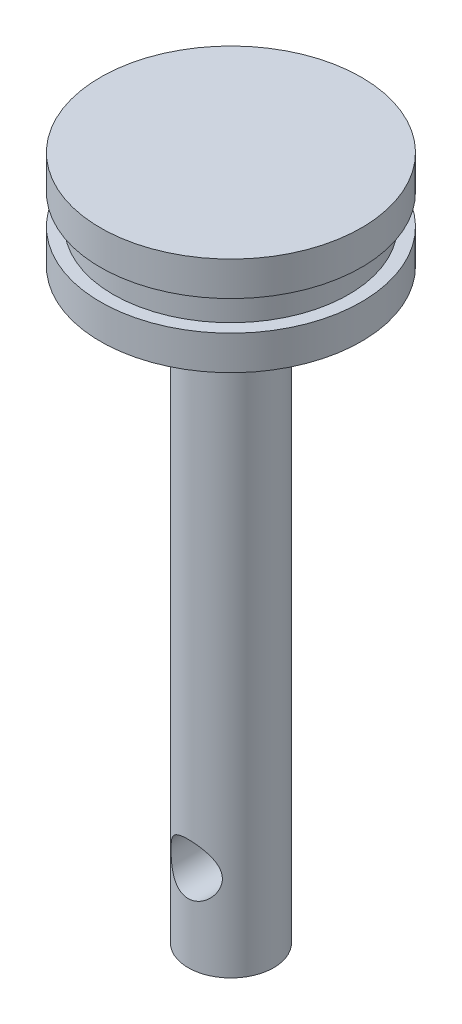
SolidWorks part; units mm, degrees
ref_plane "Front Plane" through (0, 0, 0) normal (0, 0, 1) x (1, 0, 0)
ref_plane "Top Plane" through (0, 0, 0) normal (0, 1, 0) x (1, 0, 0)
ref_plane "Right Plane" through (0, 0, 0) normal (1, 0, 0) x (0, 0, -1)
sketch "Sketch1" plane through (0, 0, 0) normal (0, 0, 1) x (1, 0, 0)
  line L0 (0, 0) -> (0, 80)
  line L1 (0, 80) -> (15.25, 80)
  line L2 (15.25, 80) -> (15.25, 76)
  line L3 (15.25, 76) -> (13.75, 76)
  line L4 (13.75, 76) -> (13.75, 72.5)
  line L5 (13.75, 72.5) -> (15.25, 72.5)
  line L6 (15.25, 72.5) -> (15.25, 68.5)
  line L7 (15.25, 68.5) -> (5, 68.5)
  line L8 (5, 68.5) -> (5, 0)
  line L9 (5, 0) -> (0, 0)
  line L10 (-25.1331, 10) -> (36.1243, 10) construction
  point P3 (15.25, 78)
  dimension "D1" = 80
  dimension "D2" = 4
  dimension "D3" = 3.5
  dimension "D4" = 4
  dimension "D5" = 5
  dimension "D6" = 15.25
  dimension "D7" = 13.75
  dimension "D8" = 15.25
  dimension "D9" = 70
revolve "Revolve2" add sketch "Sketch1" angle 360 about L0
sketch "Sketch3" plane through (0, 0, 0) normal (0, 0, 1) x (1, 0, 0)
  line L0 (15.25, 80) -> (-15.25, 80) construction
  line L1 (5, 0) -> (5, 68.5) construction
  circle A0 centre (0, 10) radius 3
  dimension "D1" = 6
  dimension "D2" = 70
  dimension "D3" = 5
extrude "Cut-Extrude1" cut sketch "Sketch3" against normal up to next and the other way up to next contours A0
